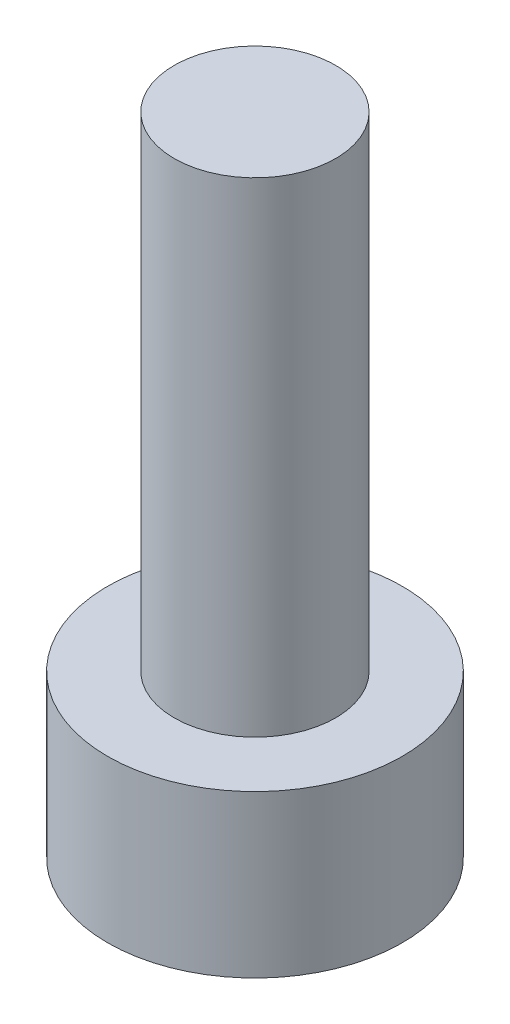
SolidWorks part; units mm, degrees
ref_plane "Front" through (0, 0, 0) normal (0, 0, 1) x (1, 0, 0)
ref_plane "Top" through (0, 0, 0) normal (0, 1, 0) x (1, 0, 0)
ref_plane "Right" through (0, 0, 0) normal (1, 0, 0) x (0, 0, -1)
sketch "草图1" plane through (0, 0, 0) normal (0, 1, 0) x (1, 0, 0)
  circle A0 centre (0, 0) radius 3.65
  dimension "D1" = 7.3
extrude "螺帽" add sketch "草图1" along normal blind 4
sketch "草图2" plane through (0, 4, 0) normal (0, 1, 0) x (1, 0, 0)
  circle A0 centre (0, 0) radius 2
  dimension "D1" = 4
extrude "螺纹" add sketch "草图2" along normal blind 12
